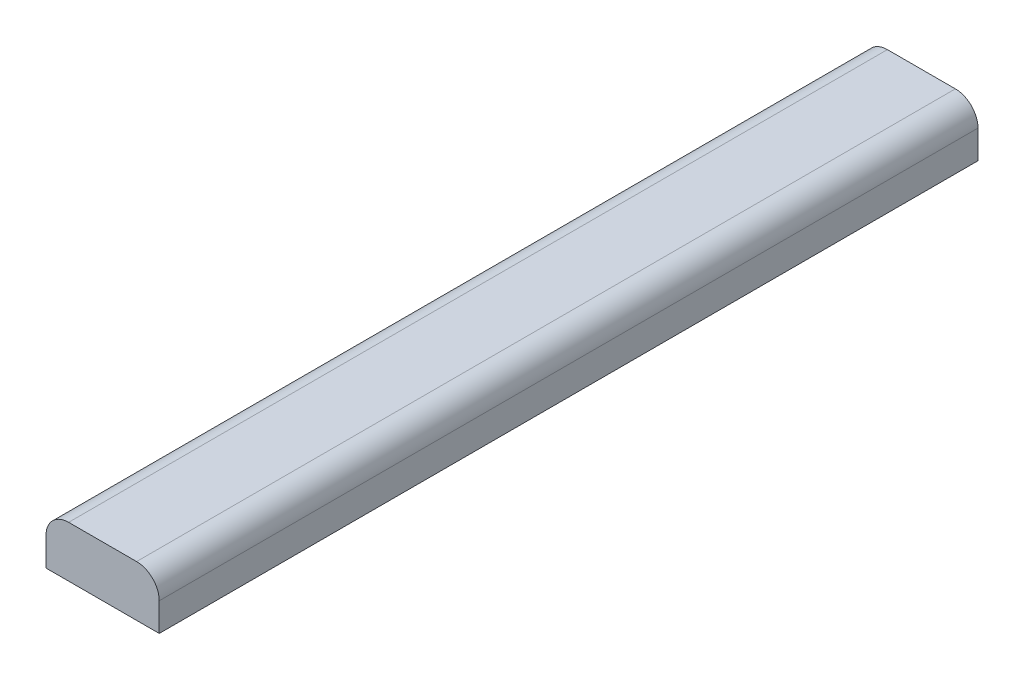
SolidWorks part; units mm, degrees
ref_plane "Front Plane" through (0, 0, 0) normal (0, 0, 1) x (1, 0, 0)
ref_plane "Top Plane" through (0, 0, 0) normal (0, 1, 0) x (1, 0, 0)
ref_plane "Right Plane" through (0, 0, 0) normal (1, 0, 0) x (0, 0, -1)
sketch "Sketch1" plane through (0, 0, 0) normal (0, 0, 1) x (1, 0, 0)
  line L1 (0, 0) -> (127, 0)
  line L2 (0, 0) -> (0, 31.75)
  line L3 (25.4, 57.15) -> (101.6, 57.15)
  line L4 (127, 0) -> (127, 31.75)
  arc A0 (101.6, 57.15) -> (127, 31.75) centre (101.6, 31.75) cw
  arc A1 (0, 31.75) -> (25.4, 57.15) centre (25.4, 31.75) cw
  point P7 (127, 57.15)
  point P10 (0, 57.15)
  dimension "D3" = 25.4
  dimension "D1" = 57.15
  dimension "D2" = 127
extrude "Boss-Extrude1" add sketch "Sketch1" along normal blind 918.21
